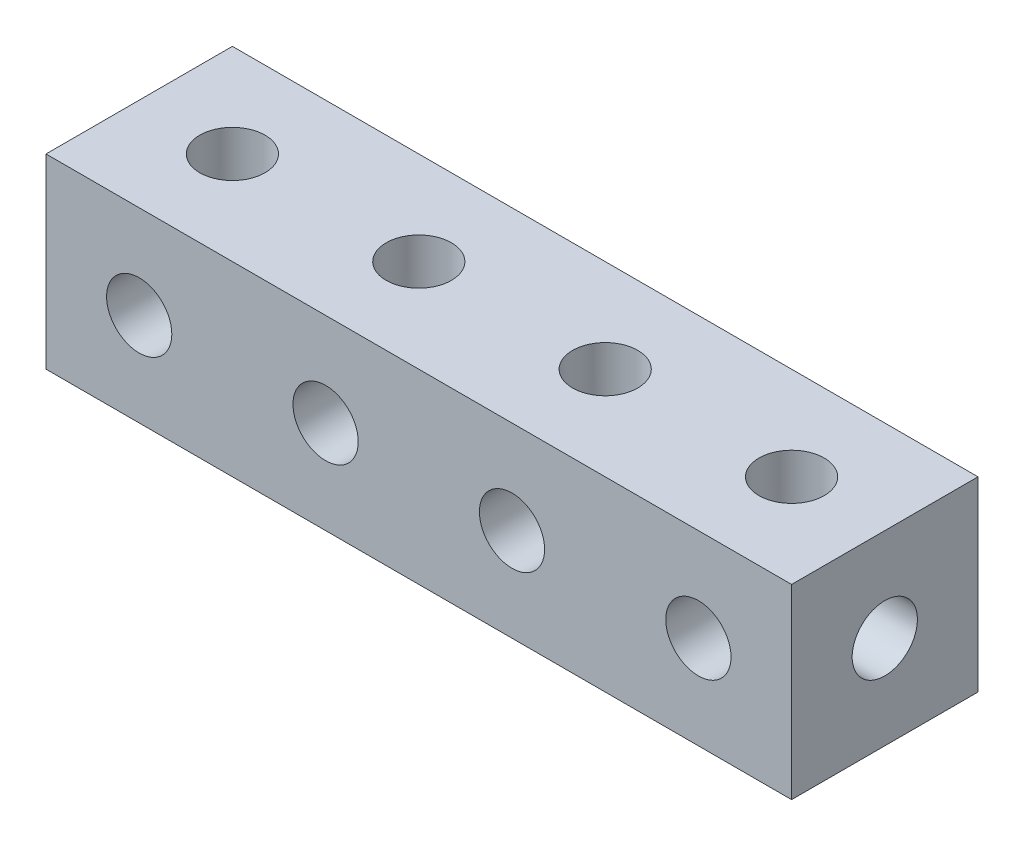
SolidWorks part; units mm, degrees
ref_plane "Plan de face" through (0, 0, 0) normal (0, 0, 1) x (1, 0, 0)
ref_plane "Plan de dessus" through (0, 0, 0) normal (0, 1, 0) x (1, 0, 0)
ref_plane "Plan de droite" through (0, 0, 0) normal (1, 0, 0) x (0, 0, -1)
sketch "Esquisse1" plane through (0, 0, 0) normal (1, 0, 0) x (0, 0, -1)
  line L1 (0, 0) -> (10, 0)
  line L2 (0, 0) -> (0, 10)
  line L3 (0, 10) -> (10, 10)
  line L4 (10, 0) -> (10, 10)
  dimension "D1" = 10
extrude "Boss.-Extru.1" add sketch "Esquisse1" along normal blind 40
sketch "Esquisse2" plane through (0, 10, 0) normal (0, 1, 0) x (1, 0, 0)
  line L0 (0, 5) -> (40, 5) construction
  line L1 (0, 10) -> (0, 0) construction
  line L2 (40, 10) -> (40, 0) construction
  circle A0 centre (5, 5) radius 1.75
  circle A1 centre (15, 5) radius 1.75
  circle A2 centre (25, 5) radius 1.75
  circle A3 centre (35, 5) radius 1.75
  dimension "D4" = 3.5
  dimension "D1" = 5
  dimension "D2" = 10
  dimension "D3" = 10
  dimension "D5" = 10
extrude "Enlèv. mat.-Extru.1" cut sketch "Esquisse2" against normal through all
sketch "Esquisse3" plane through (0, 0, 0) normal (0, 0, 1) x (1, 0, 0)
  line L0 (0, 5) -> (40, 5) construction
  line L1 (0, 10) -> (0, 0) construction
  line L2 (40, 10) -> (40, 0) construction
  circle A0 centre (5, 5) radius 1.75
  circle A1 centre (15, 5) radius 1.75
  circle A2 centre (25, 5) radius 1.75
  circle A3 centre (35, 5) radius 1.75
  dimension "D4" = 3.5
  dimension "D1" = 5
  dimension "D2" = 10
  dimension "D3" = 10
  dimension "D5" = 10
extrude "Enlèv. mat.-Extru.2" cut sketch "Esquisse3" against normal blind 40
sketch "Esquisse4" plane through (40, 0, 0) normal (1, 0, 0) x (0, 0, -1)
  line L0 (10, 10) -> (0, 0) construction
  circle A0 centre (5, 5) radius 1.75
  dimension "D1" = 3.5
extrude "Enlèv. mat.-Extru.3" cut sketch "Esquisse4" against normal blind 40
